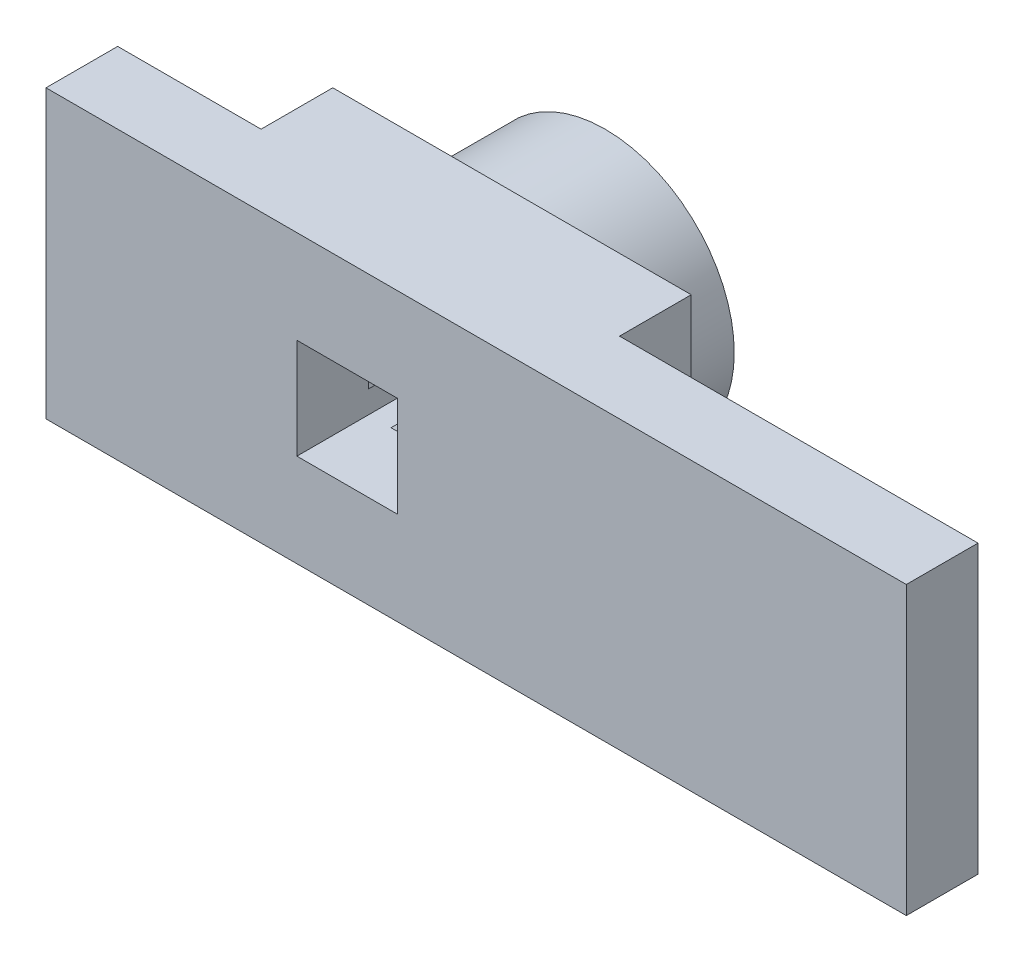
SolidWorks part; units mm, degrees
ref_plane "Front Plane" through (0, 0, 0) normal (0, 0, 1) x (1, 0, 0)
ref_plane "Top Plane" through (0, 0, 0) normal (0, 1, 0) x (1, 0, 0)
ref_plane "Right Plane" through (0, 0, 0) normal (1, 0, 0) x (0, 0, -1)
sketch "Sketch1" plane through (0, 0, 0) normal (0, 0, 1) x (1, 0, 0)
  line L1 (-60, 20) -> (0, 20)
  line L2 (-60, 20) -> (-60, 0)
  line L3 (-60, 0) -> (0, 0)
  line L4 (0, 20) -> (0, 0)
  dimension "D1" = 60
  dimension "D2" = 20
extrude "Boss-Extrude1" add sketch "Sketch1" along normal blind 10
sketch "Sketch2" plane through (0, 0, 10) normal (0, 0, 1) x (1, 0, 0)
  line L0 (-60, 0) -> (0, 0) construction
  line L1 (-42.5, 13.5) -> (-35.5, 13.5)
  line L2 (-42.5, 13.5) -> (-42.5, 6.5)
  line L3 (-42.5, 6.5) -> (-35.5, 6.5)
  line L4 (-35.5, 13.5) -> (-35.5, 6.5)
  line L5 (-60, 20) -> (-60, 0) construction
  point P4 (-39, 6.5)
  point P6 (-42.5, 10)
  dimension "D3" = 10
  dimension "D1" = 7
  dimension "D2" = 7
  dimension "D4" = 21
extrude "Cut-Extrude1" cut sketch "Sketch2" against normal blind 10
sketch "Sketch3" plane through (0, 0, 0) normal (0, -1, 0) x (-1, 0, 0)
  line L1 (25, -5) -> (0, -5)
  line L2 (25, -5) -> (25, 0)
  line L3 (25, 0) -> (0, 0)
  line L4 (0, -5) -> (0, 0)
  line L5 (25, -5) -> (0, 0) construction
  line L6 (25, 0) -> (0, -5) construction
  line L7 (60, 0) -> (50, 0)
  line L8 (60, 0) -> (60, -5)
  line L9 (60, -5) -> (50, -5)
  line L10 (50, 0) -> (50, -5)
  dimension "D1" = 25
  dimension "D2" = 10
  dimension "D3" = 5
  dimension "D4" = 5
extrude "Cut-Extrude2" cut sketch "Sketch3" against normal through all
sketch "Sketch5" plane through (0, 0, 0) normal (0, 0, -1) x (-1, 0, 0)
  line L1 (35.5, 13.5) -> (42.5, 13.5) construction
  line L2 (35.5, 6.5) -> (35.5, 13.5) construction
  circle A0 centre (39, 10) radius 9
  point P4 (37.9549, 10)
  point P7 (35.5, 10)
  dimension "D3" = 18
  dimension "D1" = 3.5
  dimension "D2" = 3.5
extrude "Boss-Extrude2" add sketch "Sketch5" along normal blind 8
sketch "Sketch6" plane through (0, 0, -8) normal (0, 0, -1) x (-1, 0, 0)
  circle A0 centre (39, 10) radius 6.51
  dimension "D1" = 13.02
extrude "Cut-Extrude3" cut sketch "Sketch6" against normal blind 5
sketch "Sketch7" plane through (0, 0, -3) normal (0, 0, -1) x (-1, 0, 0)
  circle A0 centre (39, 10) radius 4
  dimension "D1" = 8
extrude "Cut-Extrude4" cut sketch "Sketch7" against normal blind 8
